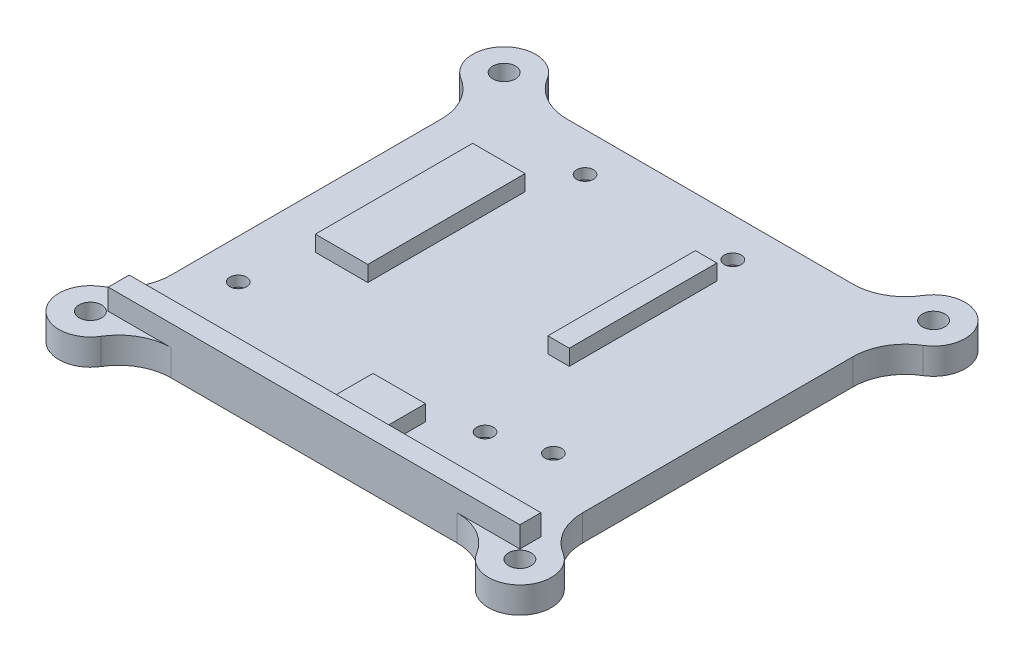
SolidWorks part; units mm, degrees
material "ABS"
ref_plane "Front Plane" through (0, 0, 0) normal (0, 0, 1) x (1, 0, 0)
ref_plane "Top Plane" through (0, 0, 0) normal (0, 1, 0) x (1, 0, 0)
ref_plane "Right Plane" through (0, 0, 0) normal (1, 0, 0) x (0, 0, -1)
sketch "Sketch1" plane through (0, 0, 0) normal (0, 1, 0) x (1, 0, 0)
  line L1 (0, 0) -> (78.5, 0)
  line L2 (0, 0) -> (0, 75.5)
  line L3 (0, 75.5) -> (78.5, 75.5)
  line L4 (78.5, 0) -> (78.5, 75.5)
  dimension "D1" = 75.5
  dimension "D2" = 78.5
extrude "Boss-Extrude1" add sketch "Sketch1" along normal blind 5
sketch "Sketch2" plane through (0, 5, 0) normal (0, 1, 0) x (1, 0, 0)
  line L0 (0, 0) -> (78.5, 0) construction
  line L1 (10, 59.5) -> (20, 59.5)
  line L2 (10, 59.5) -> (10, 29.5)
  line L3 (10, 29.5) -> (20, 29.5)
  line L4 (20, 59.5) -> (20, 29.5)
  line L9 (38.5, 12) -> (48.5, 12)
  line L10 (38.5, 12) -> (38.5, 2)
  line L11 (38.5, 2) -> (48.5, 2)
  line L12 (48.5, 12) -> (48.5, 2)
  line L13 (78.5, 0) -> (78.5, 75.5) construction
  line L14 (0, 75.5) -> (0, 0) construction
  line L19 (78.5, 75.5) -> (0, 75.5) construction
  line L21 (53.0489, 63.0179) -> (48.965, 63.0179)
  line L22 (53.0489, 63.0179) -> (53.0489, 34.872)
  line L23 (53.0489, 34.872) -> (48.965, 34.872)
  line L24 (48.965, 63.0179) -> (48.965, 34.872)
  line L25 (0, 4) -> (0, 0)
  line L26 (0, 0) -> (78.5, 0)
  line L27 (78.5, 0) -> (78.5, 4)
  line L28 (78.5, 4) -> (0, 4)
  point P29 (78.5, 2)
  dimension "D1" = 10
  dimension "D2" = 16
  dimension "D3" = 4
  dimension "D5" = 10
  dimension "D6" = 10
  dimension "D7" = 2
  dimension "D8" = 30
  dimension "D9" = 10
  dimension "D11" = 30
extrude "Boss-Extrude2" add sketch "Sketch2" along normal blind 3 contours L4 L1 L2 L3 | L21 L24 L23 L22 | L28 L12 L9 L10
sketch "Sketch4" plane through (0, 5, 0) normal (0, 1, 0) x (1, 0, 0)
  line L3 (5, 2) -> (73.5, 2)
  line L4 (0, 0) -> (78.5, 0) construction
  line L5 (78.5, 0) -> (78.5, 75.5) construction
  line L6 (73.5, 70.5) -> (5, 70.5)
  line L7 (73.5, 0) -> (73.5, 70.5)
  line L8 (5, 70.5) -> (5, 0)
  line L9 (73.5, 70.5) -> (5, 70.5)
  line L10 (73.5, 2) -> (73.5, 70.5)
  line L11 (5, 70.5) -> (5, 2)
  line L12 (78.5, 75.5) -> (0, 75.5) construction
  line L13 (0, 75.5) -> (0, 0) construction
  line L14 (78.5, 0) -> (78.5, 75.5)
  line L15 (78.5, 75.5) -> (0, 75.5)
  line L16 (0, 75.5) -> (0, 0)
  line L17 (0, 0) -> (78.5, 0)
  dimension "D2" = 2
  dimension "D1" = 5
sketch "Sketch6" plane through (0, 0, 0) normal (0, 1, 0) x (1, 0, 0)
  line L0 (0, 0) -> (78.5, 0) construction
  line L1 (-5.2236, 37.75) -> (88.1951, 37.75) construction
  line L2 (39.25, 80.592) -> (39.25, -11.8598) construction
  line L3 (0, 0) -> (0, 4.0541)
  line L4 (0, 0) -> (0, 75.5) construction
  line L5 (0, 0) -> (4.0541, 0)
  line L9 (78.5, 0) -> (74.4459, 0)
  line L15 (78.5, 0) -> (78.5, 4.0541)
  line L16 (78.5, 75.5) -> (78.5, 71.4459)
  line L17 (78.5, 75.5) -> (74.4459, 75.5)
  line L18 (0, 75.5) -> (4.0541, 75.5)
  line L19 (0, 75.5) -> (0, 71.4459)
  arc A0 (0, 4.0541) -> (4.0541, 0) centre (-1.7, -1.7) ccw
  circle A2 centre (-1.7, -1.7) radius 2.15
  circle A18 centre (80.2, -1.7) radius 2.15
  arc A19 (78.5, 4.0541) -> (74.4459, 0) centre (80.2, -1.7) cw
  arc A20 (78.5, 71.4459) -> (74.4459, 75.5) centre (80.2, 77.2) ccw
  circle A21 centre (80.2, 77.2) radius 2.15
  circle A22 centre (-1.7, 77.2) radius 2.15
  arc A23 (0, 71.4459) -> (4.0541, 75.5) centre (-1.7, 77.2) cw
  dimension "D1" = 4.3
  dimension "D2" = 6
  dimension "D3" = 1.7
  dimension "D4" = 1.7
extrude "Boss-Extrude3" add sketch "Sketch6" along normal blind 5 contours L3 A0 L5 A2 | A19 L15 L9 A18 | A23 L19 L18 A22 | L16 A20 L17 A21
sketch "Sketch7" plane through (0, 0, 0) normal (0, 1, 0) x (1, 0, 0)
  line L0 (0, 0) -> (0, 75.5) construction
  line L1 (0, 27.9816) -> (0, 4.0541)
  line L2 (-11.9134, 14.9098) -> (0, 27.9816)
  line L3 (37.8296, -8.4702) -> (37.8296, 85.7453) construction
  line L4 (87.5725, 14.9098) -> (75.6591, 27.9816)
  line L5 (75.6591, 27.9816) -> (75.6591, 4.0541)
  line L6 (-8.2378, 37.75) -> (82.9655, 37.75) construction
  line L7 (75.6591, 47.5184) -> (75.6591, 71.4459)
  line L8 (87.5725, 60.5902) -> (75.6591, 47.5184)
  line L9 (-11.9134, 60.5902) -> (0, 47.5184)
  line L10 (0, 47.5184) -> (0, 71.4459)
  circle A0 centre (-8.2179, 11.5418) radius 2.25
  circle A1 centre (-8.2179, 11.5418) radius 5
  circle A2 centre (-1.7, -1.7) radius 6 construction
  arc A3 (0, 4.0541) -> (-7.4134, 0.1321) centre (-1.7, -1.7) ccw
  arc A4 (75.6591, 4.0541) -> (83.0726, 0.1321) centre (77.3591, -1.7) cw
  circle A5 centre (83.877, 11.5418) radius 5
  circle A6 centre (83.877, 11.5418) radius 2.25
  circle A7 centre (83.877, 63.9582) radius 2.25
  circle A8 centre (83.877, 63.9582) radius 5
  arc A9 (75.6591, 71.4459) -> (83.0726, 75.3679) centre (77.3591, 77.2) ccw
  arc A10 (0, 71.4459) -> (-7.4134, 75.3679) centre (-1.7, 77.2) cw
  circle A11 centre (-8.2179, 63.9582) radius 5
  circle A12 centre (-8.2179, 63.9582) radius 2.25
  spline S0 degree 3 poles (-7.4134, 0.1321) (-7.4383, 1.2594) (-8.3204, 5.0324) (-9.7398, 6.7791) knots 0.392274 0.392274 0.392274 0.392274 1 1 1 1
  spline S1 degree 3 poles (83.0726, 0.1321) (83.0974, 1.2594) (83.9796, 5.0324) (85.3989, 6.7791) knots 0.392274 0.392274 0.392274 0.392274 1 1 1 1
  spline S2 degree 3 poles (83.0726, 75.3679) (83.0974, 74.2406) (83.9796, 70.4676) (85.3989, 68.7209) knots 0.392274 0.392274 0.392274 0.392274 1 1 1 1
  spline S3 degree 3 poles (-7.4134, 75.3679) (-7.4383, 74.2406) (-8.3204, 70.4676) (-9.7398, 68.7209) knots 0.392274 0.392274 0.392274 0.392274 1 1 1 1
  dimension "D1" = 4.5
  dimension "D2" = 10
extrude "Boss-Extrude4" [suppressed] add sketch "Sketch7" along normal blind 5 contours S0 A3 L1 L2 A1 | S0 A1 A0 | A4 S1 A5 L4 L5 | A5 S1 A6 | A10 S3 A11 L9 L10 | A11 S3 A12 | S2 A9 L7 L8 A8 | S2 A8 A7
sketch "Sketch8" plane through (0, 0, 0) normal (0, -1, 0) x (1, 0, 0)
  line L0 (39.25, 0) -> (39.25, -81.199) construction
  line L1 (0, 0) -> (78.5, 0) construction
  line L2 (0, -37.75) -> (81.8718, -37.75) construction
  line L3 (0, 0) -> (0, -75.5) construction
  circle A0 centre (-1.7, 1.7) radius 4
  circle A1 centre (80.2, 1.7) radius 4
  circle A2 centre (80.2, -77.2) radius 4
  circle A3 centre (-1.7, -77.2) radius 4
  dimension "D1" = 8
extrude "Cut-Extrude5" [suppressed] cut sketch "Sketch8" against normal blind 3
sketch "Sketch3" plane through (0, 5, 0) normal (0, 1, 0) x (1, 0, 0)
  circle A0 centre (7.54, 17.25) radius 1.6
  circle A1 centre (55.86, 16) radius 1.6
  circle A2 centre (22.87, 68.06) radius 1.6
  circle A3 centre (51.04, 68.06) radius 1.6
  circle A6 centre (7.54, 17.25) radius 1.6 construction
  circle A7 centre (55.86, 16) radius 1.5 construction
  circle A10 centre (65.9, 19) radius 1.6
  circle A11 centre (65.9, 19) radius 1.5 construction
  circle A15 centre (22.87, 68.06) radius 1.6 construction
  circle A16 centre (51.04, 68.06) radius 1.6 construction
  dimension "D1" = 3.2
extrude "Cut-Extrude3" cut sketch "Sketch3" against normal blind 10
sketch "Sketch5" plane through (0, 0, 0) normal (0, -1, 0) x (1, 0, 0)
  circle A0 centre (7.54, -17.25) radius 3.25
  circle A1 centre (55.86, -16) radius 3.25
  circle A2 centre (22.87, -68.06) radius 3.25
  circle A3 centre (51.04, -68.06) radius 3.25
  circle A4 centre (65.9, -19) radius 3.25
  circle A5 centre (65.9, -19) radius 1.5 construction
  dimension "D1" = 6.5
extrude "Cut-Extrude4" cut sketch "Sketch5" against normal blind 3
sketch "Sketch9" plane through (0, 5, 0) normal (0, 1, 0) x (1, 0, 0)
  line L28 (0, 4) -> (0, 0)
  line L29 (0, 0) -> (78.5, 0)
  line L30 (78.5, 0) -> (78.5, 4)
  line L31 (78.5, 4) -> (0, 4)
  line L32 (0, 4) -> (0, 0)
  line L33 (0, 0) -> (78.5, 0)
  line L34 (78.5, 0) -> (78.5, 4)
  line L35 (78.5, 4) -> (0, 4)
  dimension "D4" = 0
extrude "Boss-Extrude5" add sketch "Sketch9" along normal blind 4
fillet "Fillet2" radius 10 1 edges at (4.0541, 2.5, 0)
fillet "Fillet3" radius 10 1 edges at (74.4459, 2.5, 0)
fillet "Fillet4" radius 10 1 edges at (78.5, 2.5, -4.0541)
fillet "Fillet5" radius 10 1 edges at (78.5, 2.5, -71.4459)
fillet "Fillet6" radius 10 1 edges at (74.4459, 2.5, -75.5)
fillet "Fillet7" radius 10 1 edges at (4.0541, 2.5, -75.5)
fillet "Fillet8" radius 10 1 edges at (0, 2.5, -71.4459)
fillet "Fillet9" radius 10 1 edges at (0, 2.5, -4.0541)
